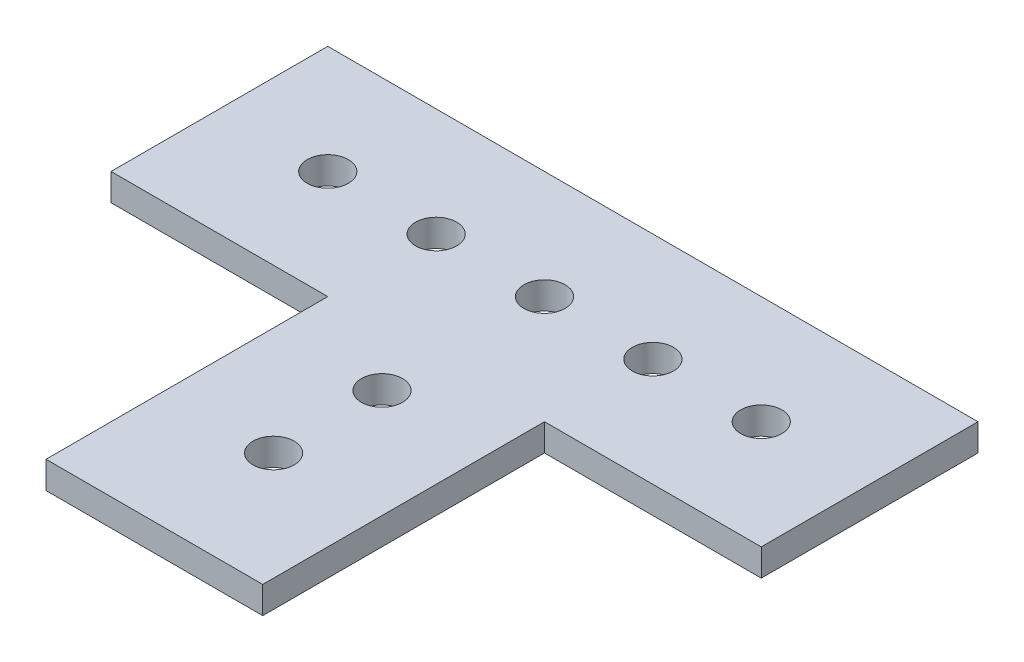
SolidWorks part; units mm, degrees
ref_plane "Front Plane" through (0, 0, 0) normal (0, 0, 1) x (1, 0, 0)
ref_plane "Top Plane" through (0, 0, 0) normal (0, 1, 0) x (1, 0, 0)
ref_plane "Right Plane" through (0, 0, 0) normal (1, 0, 0) x (0, 0, -1)
sketch "Sketch2" plane through (0, 0, 0) normal (0, 1, 0) x (1, 0, 0)
  line L0 (25.4, 33.02) -> (50.8, 33.02)
  line L1 (0, 0) -> (25.4, 0)
  line L2 (0, 0) -> (0, 33.02)
  line L4 (25.4, 0) -> (25.4, 33.02)
  line L5 (-25.4, 33.02) -> (0, 33.02)
  line L6 (-25.4, 33.02) -> (-25.4, 58.42)
  line L7 (-25.4, 58.42) -> (50.8, 58.42)
  line L8 (50.8, 33.02) -> (50.8, 58.42)
  dimension "D1" = 58.42
  dimension "D2" = 76.2
  dimension "D3" = 25.4
  dimension "D4" = 25.4
extrude "Boss-Extrude1" add sketch "Sketch2" along normal blind 3.175
sketch "Sketch3" plane through (0, 3.175, 0) normal (0, 1, 0) x (1, 0, 0)
  line L0 (12.7, 0) -> (12.7, 58.42) construction
  line L1 (0, 0) -> (25.4, 0) construction
  line L2 (50.8, 58.42) -> (-25.4, 58.42) construction
  line L3 (-25.4, 45.72) -> (50.8, 45.72) construction
  line L4 (-25.4, 58.42) -> (-25.4, 33.02) construction
  line L5 (50.8, 33.02) -> (50.8, 58.42) construction
  circle A0 centre (12.7, 13.97) radius 2.413
  circle A1 centre (-12.7, 45.72) radius 2.413
  circle A2 centre (12.7, 26.67) radius 2.413
  circle A3 centre (0, 45.72) radius 2.413
  circle A4 centre (12.7, 45.72) radius 2.413
  circle A5 centre (25.4, 45.72) radius 2.413
  circle A6 centre (38.1, 45.72) radius 2.413
  dimension "D1" = 4.826
  dimension "D2" = 4.826
  dimension "D3" = 13.97
  dimension "D5" = 12.7
  dimension "D4" = 2
  dimension "D6" = 5
extrude "Cut-Extrude1" cut sketch "Sketch3" against normal through all
